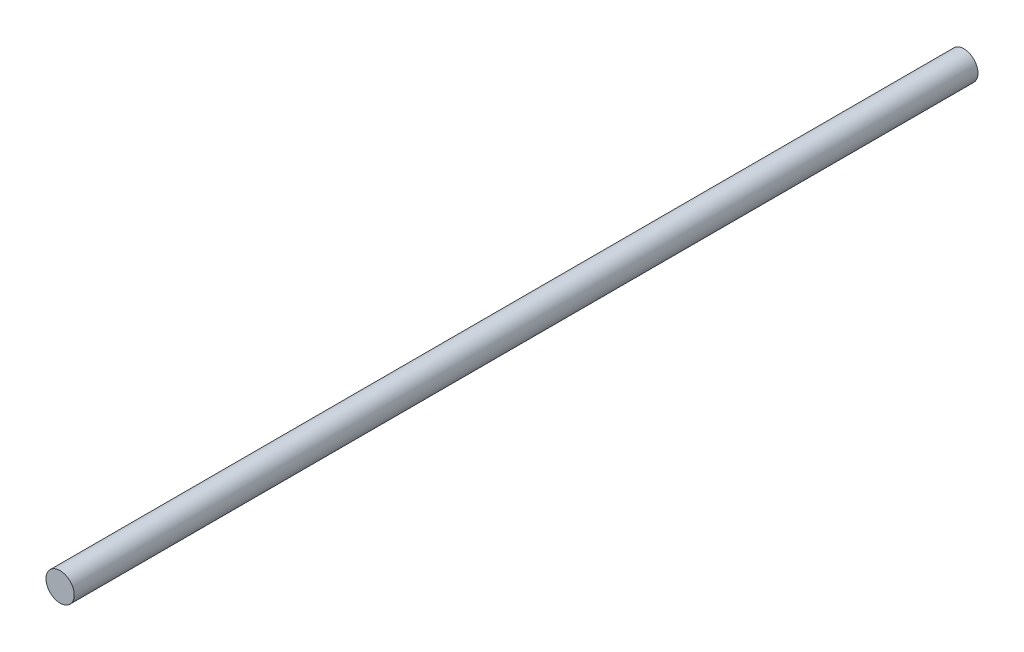
SolidWorks part; units mm, degrees
ref_plane "前视基准面" through (0, 0, 0) normal (0, 0, 1) x (1, 0, 0)
ref_plane "上视基准面" through (0, 0, 0) normal (0, 1, 0) x (1, 0, 0)
ref_plane "右视基准面" through (0, 0, 0) normal (1, 0, 0) x (0, 0, -1)
sketch "草图1" plane through (0, 0, 0) normal (0, 0, 1) x (1, 0, 0)
  circle A0 centre (0, 0) radius 2.5
extrude "凸台-拉伸1" add sketch "草图1" along normal blind 160
